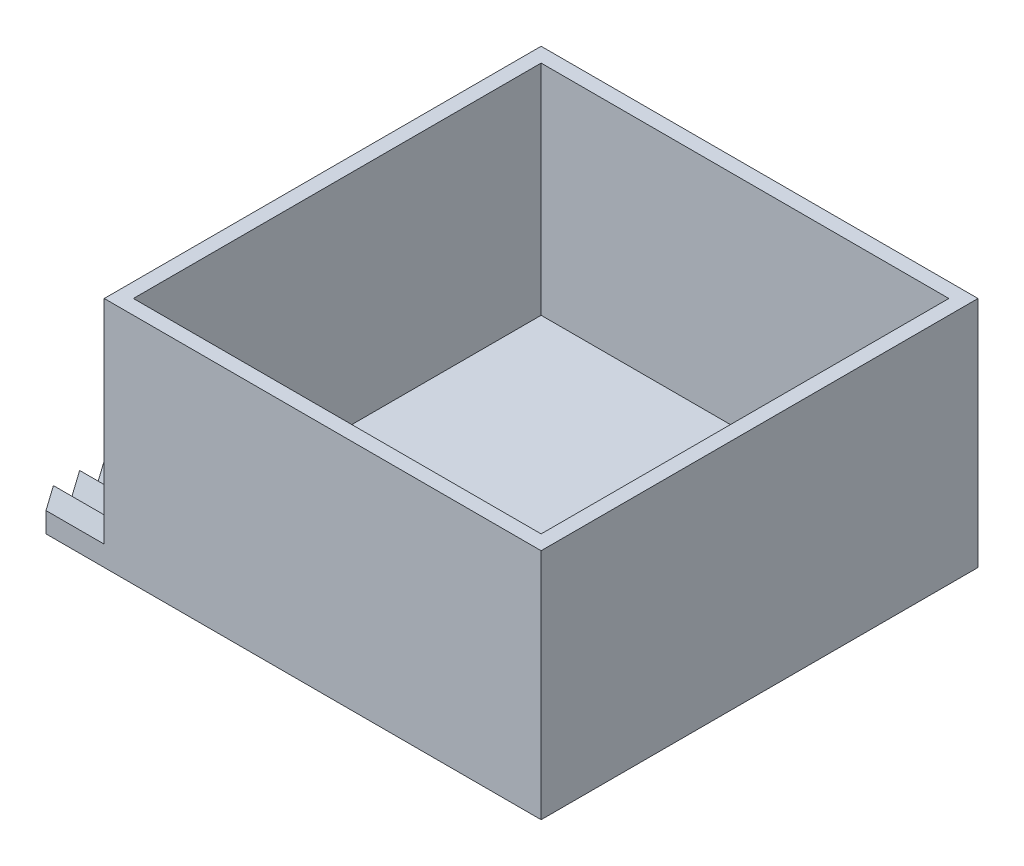
SolidWorks part; units mm, degrees
ref_plane "Front Plane" through (0, 0, 0) normal (0, 0, 1) x (1, 0, 0)
ref_plane "Top Plane" through (0, 0, 0) normal (0, 1, 0) x (1, 0, 0)
ref_plane "Right Plane" through (0, 0, 0) normal (1, 0, 0) x (0, 0, -1)
sketch "Sketch1" plane through (0, 0, 0) normal (0, 1, 0) x (1, 0, 0)
  line L1 (7.5, 7.5) -> (-7.5, 7.5)
  line L2 (7.5, 7.5) -> (7.5, -7.5)
  line L3 (7.5, -7.5) -> (-7.5, -7.5)
  line L4 (-7.5, 7.5) -> (-7.5, -7.5)
  line L5 (7.5, 7.5) -> (-7.5, -7.5) construction
  line L6 (7.5, -7.5) -> (-7.5, 7.5) construction
  point P0 (0, 0)
  dimension "D1" = 15
  dimension "D2" = 15
extrude "Boss-Extrude1" add sketch "Sketch1" along normal blind 8
shell "Shell6" thickness 0.5
sketch "Sketch2" plane through (-7.5, 0, 0) normal (-1, 0, 0) x (0, 0, 1)
  line L0 (-7.5, 0) -> (7.5, 0)
  line L1 (7.5, 0) -> (7.5, 0.5)
  line L2 (7.5, 8) -> (7.5, 0) construction
  line L3 (6.9, 0.5) -> (6.6801, 0.5)
  line L4 (-7.5, 8) -> (-7.5, 0) construction
  line L5 (-7.5, 0.5) -> (-7.5, 0)
  line L6 (-7.5, 0.5) -> (-7.1546, 1.3094)
  line L7 (-7.1546, 1.3094) -> (-6.8199, 0.5)
  line L8 (-6.6, 0.5) -> (-6.2546, 1.3094)
  line L9 (-6.2546, 1.3094) -> (-5.9199, 0.5)
  line L10 (-5.7, 0.5) -> (-5.3546, 1.3094)
  line L11 (-5.3546, 1.3094) -> (-5.0199, 0.5)
  line L12 (-4.8, 0.5) -> (-4.4546, 1.3094)
  line L13 (-4.4546, 1.3094) -> (-4.1199, 0.5)
  line L14 (-3.9, 0.5) -> (-3.5546, 1.3094)
  line L15 (-3.5546, 1.3094) -> (-3.2199, 0.5)
  line L16 (-3, 0.5) -> (-2.6546, 1.3094)
  line L17 (-2.6546, 1.3094) -> (-2.3199, 0.5)
  line L18 (-2.1, 0.5) -> (-1.7546, 1.3094)
  line L19 (-1.7546, 1.3094) -> (-1.4199, 0.5)
  line L20 (-1.2, 0.5) -> (-0.8546, 1.3094)
  line L21 (-0.8546, 1.3094) -> (-0.5199, 0.5)
  line L22 (-0.3, 0.5) -> (0.0454, 1.3094)
  line L23 (0.0454, 1.3094) -> (0.3801, 0.5)
  line L24 (0.6, 0.5) -> (0.9454, 1.3094)
  line L25 (0.9454, 1.3094) -> (1.2801, 0.5)
  line L26 (1.5, 0.5) -> (1.8454, 1.3094)
  line L27 (1.8454, 1.3094) -> (2.1801, 0.5)
  line L28 (2.4, 0.5) -> (2.7454, 1.3094)
  line L29 (2.7454, 1.3094) -> (3.0801, 0.5)
  line L30 (3.3, 0.5) -> (3.6454, 1.3094)
  line L31 (3.6454, 1.3094) -> (3.9801, 0.5)
  line L32 (4.2, 0.5) -> (4.5454, 1.3094)
  line L33 (4.5454, 1.3094) -> (4.8801, 0.5)
  line L34 (5.1, 0.5) -> (5.4454, 1.3094)
  line L35 (5.4454, 1.3094) -> (5.7801, 0.5)
  line L36 (6, 0.5) -> (6.3454, 1.3094)
  line L37 (6.3454, 1.3094) -> (6.6801, 0.5)
  line L38 (6.9, 0.5) -> (7.2454, 1.3094) construction
  line L39 (7.2454, 1.3094) -> (7.5, 0.6937) construction
  line L40 (-6.8199, 0.5) -> (-7.5, 0.5) construction
  line L41 (-6.6, 0.5) -> (-6.8199, 0.5)
  line L42 (-5.9199, 0.5) -> (-6.6, 0.5) construction
  line L43 (-5.7, 0.5) -> (-5.9199, 0.5)
  line L44 (-5.0199, 0.5) -> (-5.7, 0.5) construction
  line L45 (-4.8, 0.5) -> (-5.0199, 0.5)
  line L46 (-4.1199, 0.5) -> (-4.8, 0.5) construction
  line L47 (-3.9, 0.5) -> (-4.1199, 0.5)
  line L48 (-3.2199, 0.5) -> (-3.9, 0.5) construction
  line L49 (-3, 0.5) -> (-3.2199, 0.5)
  line L50 (-2.3199, 0.5) -> (-3, 0.5) construction
  line L51 (-2.1, 0.5) -> (-2.3199, 0.5)
  line L52 (-1.4199, 0.5) -> (-2.1, 0.5) construction
  line L53 (-1.2, 0.5) -> (-1.4199, 0.5)
  line L54 (-0.5199, 0.5) -> (-1.2, 0.5) construction
  line L55 (-0.3, 0.5) -> (-0.5199, 0.5)
  line L56 (0.3801, 0.5) -> (-0.3, 0.5) construction
  line L57 (0.6, 0.5) -> (0.3801, 0.5)
  line L58 (1.2801, 0.5) -> (0.6, 0.5) construction
  line L59 (1.5, 0.5) -> (1.2801, 0.5)
  line L60 (2.1801, 0.5) -> (1.5, 0.5) construction
  line L61 (2.4, 0.5) -> (2.1801, 0.5)
  line L62 (3.0801, 0.5) -> (2.4, 0.5) construction
  line L63 (3.3, 0.5) -> (3.0801, 0.5)
  line L64 (3.9801, 0.5) -> (3.3, 0.5) construction
  line L65 (4.2, 0.5) -> (3.9801, 0.5)
  line L66 (4.8801, 0.5) -> (4.2, 0.5) construction
  line L67 (5.1, 0.5) -> (4.8801, 0.5)
  line L68 (5.7801, 0.5) -> (5.1, 0.5) construction
  line L69 (6, 0.5) -> (5.7801, 0.5)
  line L70 (6.6801, 0.5) -> (6, 0.5) construction
  line L71 (7.5, 0.6937) -> (7.5, 0.5)
  line L72 (7.5, 0.5) -> (6.9, 0.5) construction
  line L75 (7.5, 0.6937) -> (7.5, 0.5)
  line L76 (6.9, 0.5) -> (7.2454, 1.3094)
  line L77 (7.2454, 1.3094) -> (7.5, 0.6937)
  dimension "D1" = 0.5
  dimension "D2" = 0.8759
  dimension "D3" = 0.88
  dimension "D4" = 0.8094
  dimension "D5" = 17
extrude "Boss-Extrude3" add sketch "Sketch2" along normal blind 2 contours L77 L76 L3 L37 L36 L69 L35 L34 L67 L33 L32 L65 L31 L30 L63 L29 L28 L61 L27 L26 L59 L25 L24 L57 L23 L22 L55 L21 L20 L53 L19 L18 L51 L17 L16 L49 L15 L14 L47 L13 L12 L45 L11 L10 L43 L9 L8 L41 L7 L6 L5 L0 L1 L75
